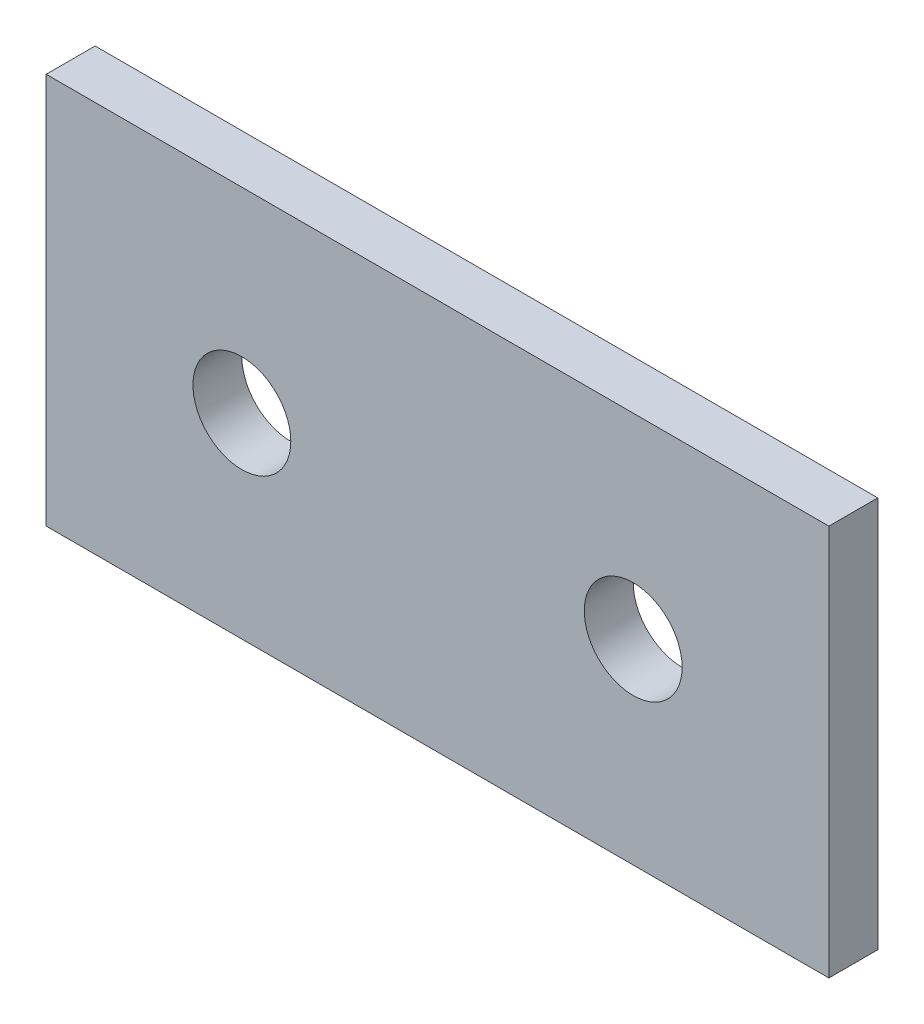
SolidWorks part; units mm, degrees
ref_plane "Front Plane" through (0, 0, 0) normal (0, 0, 1) x (1, 0, 0)
ref_plane "Top Plane" through (0, 0, 0) normal (0, 1, 0) x (1, 0, 0)
ref_plane "Right Plane" through (0, 0, 0) normal (1, 0, 0) x (0, 0, -1)
sketch "Sketch1" plane through (0, 0, 0) normal (0, 0, 1) x (1, 0, 0)
  line L1 (0, 0) -> (50.8, 0)
  line L2 (0, 0) -> (0, 25.4)
  line L3 (0, 25.4) -> (50.8, 25.4)
  line L4 (50.8, 0) -> (50.8, 25.4)
  dimension "D1" = 50.8
  dimension "D2" = 25.4
extrude "Boss-Extrude1" add sketch "Sketch1" along normal blind 3.175
sketch "Sketch2" plane through (0, 0, 3.175) normal (0, 0, 1) x (1, 0, 0)
  line L0 (50.8, 0) -> (50.8, 25.4) construction
  line L3 (0, 0) -> (50.8, 0) construction
  circle A0 centre (12.7, 12.7) radius 3.175
  circle A1 centre (38.1, 12.7) radius 3.175
  dimension "D1" = 6.35
  dimension "D4" = 6.35
  dimension "D2" = 25.4
  dimension "D3" = 12.7
  dimension "D5" = 12.7
extrude "Cut-Extrude1" cut sketch "Sketch2" against normal up to surface (3.175 mm away) contours A0 | A1
